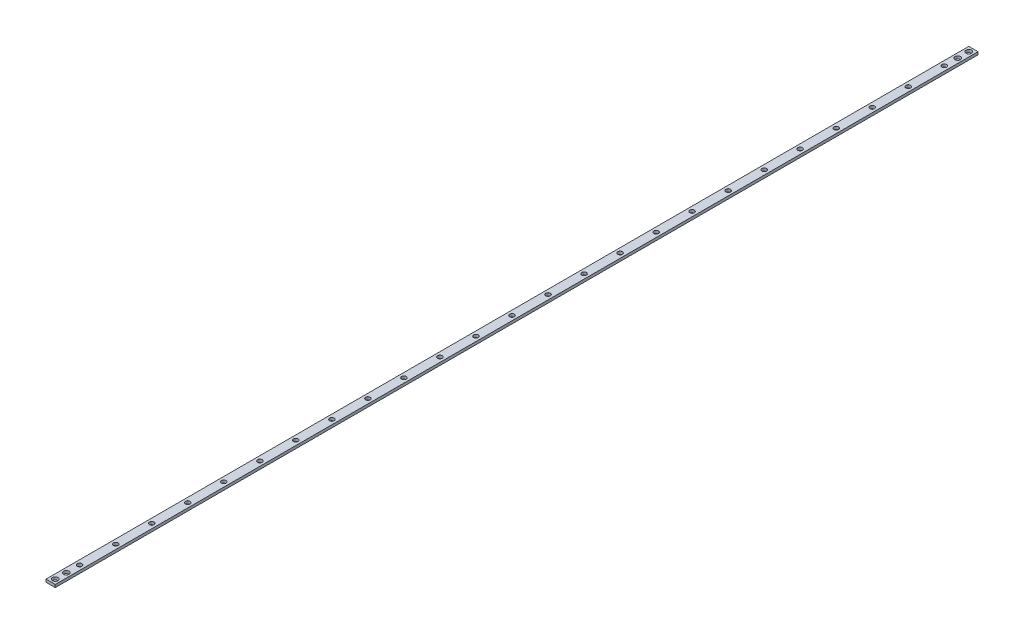
SolidWorks part; units mm, degrees
ref_plane "Front Plane" through (0, 0, 0) normal (0, 0, 1) x (1, 0, 0)
ref_plane "Top Plane" through (0, 0, 0) normal (0, 1, 0) x (1, 0, 0)
ref_plane "Right Plane" through (0, 0, 0) normal (1, 0, 0) x (0, 0, -1)
sketch "Sketch1" plane through (0, 0, 0) normal (0, 1, 0) x (1, 0, 0)
  line L0 (0, 0) -> (0, 1000)
  line L1 (0, 0) -> (10, 0)
  line L2 (0, 1000) -> (10, 1000)
  line L3 (10, 0) -> (10, 1000)
  dimension "Rail Length" = 1000
  dimension "Rail Width" = 10
extrude "Boss-Extrude1" add sketch "Sketch1" along normal blind 3
sketch "Sketch11" plane through (0, 3, 0) normal (0, 1, 0) x (1, 0, 0)
  line L0 (0, 0) -> (10, 0) construction
  line L1 (0, 1000) -> (0, 0) construction
  line L2 (10, 1000) -> (0, 1000) construction
  line L3 (10, 0) -> (10, 1000) construction
  point P0 (5, 5)
  point P6 (5, 995)
  dimension "B End Spacing ~ Feature Holes" = 5
  dimension "B Centre on Rail ~ Feature Holes" = 5
  dimension "A End Spacing ~ Feature Holes" = 5
  dimension "A Centre on Rail ~ Feature Holes" = 5
hole_wizard "Tap Drill for M7x1.0 Tap1" positions "Sketch12" profile "Sketch13" hole size "M7x1.0" standard "ISO" end condition through all
sketch "Sketch12" plane through (0, 0, 0) normal (0, -1, 0) x (-1, 0, 0)
  point P0 (-5, 5)
sketch "Sketch13" plane through (5, 0, -5) normal (1, 0, 0) x (0, 0, -1)
  line L0 (0, 0) -> (0, 3)
  line L1 (0, 3) -> (3, 3)
  line L2 (3, 3) -> (3, 0.025)
  line L3 (3, 0.025) -> (3.025, 0)
  line L5 (3.025, 0) -> (0, 0)
  line L6 (-3, 0.025) -> (-3.025, 0) construction
  line L11 (0, -6.35) -> (0, 107.95) construction
  dimension "Thru Hole Dia." = 6
  dimension "Thru Hole Depth" = 3
  dimension "Near C'Sink Dia." = 6.05
  dimension "Near C'Sink Angle" = 90
pattern_linear "LPattern2" count 2 spacing 12 along (0, 0, -1) of "Tap Drill for M7x1.0 Tap1"
hole_wizard "Tap Drill for M7x1.0 Tap2" positions "Sketch14" profile "Sketch15" hole size "M7x1.0" standard "ISO" end condition through all
sketch "Sketch14" plane through (0, 0, 0) normal (0, -1, 0) x (-1, 0, 0)
  point P0 (-5, 995)
sketch "Sketch15" plane through (5, 0, -995) normal (1, 0, 0) x (0, 0, -1)
  line L0 (0, 0) -> (0, 3)
  line L1 (0, 3) -> (3, 3)
  line L2 (3, 3) -> (3, 0.025)
  line L3 (3, 0.025) -> (3.025, 0)
  line L5 (3.025, 0) -> (0, 0)
  line L6 (-3, 0.025) -> (-3.025, 0) construction
  line L11 (0, -6.35) -> (0, 107.95) construction
  dimension "Thru Hole Dia." = 6
  dimension "Thru Hole Depth" = 3
  dimension "Near C'Sink Dia." = 6.05
  dimension "Near C'Sink Angle" = 90
pattern_linear "LPattern3" count 2 spacing 12 along (0, 0, 1) of "Tap Drill for M7x1.0 Tap2"
sketch "Sketch8" plane through (0, 3, 0) normal (0, 1, 0) x (1, 0, 0)
  line L0 (0, 0) -> (10, 0) construction
  line L1 (10, 0) -> (10, 1000) construction
  point P0 (5, 31.5)
  dimension "Dist. from End" = 31.5
  dimension "Centre on Rail" = 5
hole_wizard "Ø5.0mm Dowel Hole1" positions "Sketch9" profile "Sketch10" hole size "Ø5.0" standard "ISO" end condition through all
sketch "Sketch9" plane through (0, 3, 0) normal (0, 1, 0) x (1, 0, 0)
  point P0 (5, 31.5)
sketch "Sketch10" plane through (5, 3, -31.5) normal (1, 0, 0) x (0, 0, 1)
  line L0 (0, 0) -> (0, 3)
  line L1 (0, 3) -> (2.5, 3)
  line L2 (2.5, 3) -> (2.5, 0.025)
  line L3 (2.5, 0.025) -> (2.525, 0)
  line L5 (2.525, 0) -> (0, 0)
  line L6 (-2.5, 0.025) -> (-2.525, 0) construction
  line L11 (0, -6.35) -> (0, 107.95) construction
  dimension "Thru Hole Dia." = 5
  dimension "Thru Hole Depth" = 3
  dimension "Near C'Sink Dia." = 5.05
  dimension "Near C'Sink Angle" = 90
pattern_linear "LPattern1" count 25 spacing 39.0417 along (0, 0, -1) of "Ø5.0mm Dowel Hole1"
equation "\"Rail Length\"= 1000"
equation "\"Rail Width\"= 10"
equation "\"Rail Thickness\"= 3"
equation "\"Number of Holes\"= 25"
equation "\"Feature Hole Spacing from End\"= 5"
equation "\"Number of Feature Holes\"= 2"
equation "\"Spacing of Feature Holes\"= 12"
equation "\"Rail Length@Sketch1\"= \"Rail Length\""
equation "\"Rail Width@Sketch1\"= \"Rail Width\""
equation "\"Rail Thickness@Boss-Extrude1\"= \"Rail Thickness\""
equation "\"No. Holes@LPattern1\"= \"Number of Holes\""
equation "\"Dist. from End@Sketch8\" = \"Feature Hole Spacing from End\" + ( \"Number of Feature Holes\" * \"Spacing of Feature Holes\" ) + ( \"Thru Hole Dia.@Sketch10\" / 2 )"
equation "\"Centre on Rail@Sketch8\" = \"Rail Width@Sketch1\" / 2"
equation "\"Hole Spacing@LPattern1\"= ( \"Rail Length@Sketch1\" - ( 2 * \"Dist. from End@Sketch8\" ) ) / ( \"No. Holes@LPattern1\" - 1 )"
equation "\"A Centre on Rail ~ Feature Holes@Sketch11\"= \"Rail Width@Sketch1\" / 2"
equation "\"B Centre on Rail ~ Feature Holes@Sketch11\" = \"A Centre on Rail ~ Feature Holes@Sketch11\""
equation "\"A End Spacing ~ Feature Holes@Sketch11\" = \"Feature Hole Spacing from End\""
equation "\"B End Spacing ~ Feature Holes@Sketch11\"= \"A End Spacing ~ Feature Holes@Sketch11\""
equation "\"A Hole Spacing ~ Feature Holes@LPattern3\"= \"Spacing of Feature Holes\""
equation "\"B Hole Spacing ~ Feature Holes@LPattern2\"= \"Spacing of Feature Holes\""
equation "\"D1@LPattern2\" = \"Number of Feature Holes\""
equation "\"D1@LPattern3\"= \"D1@LPattern2\""
